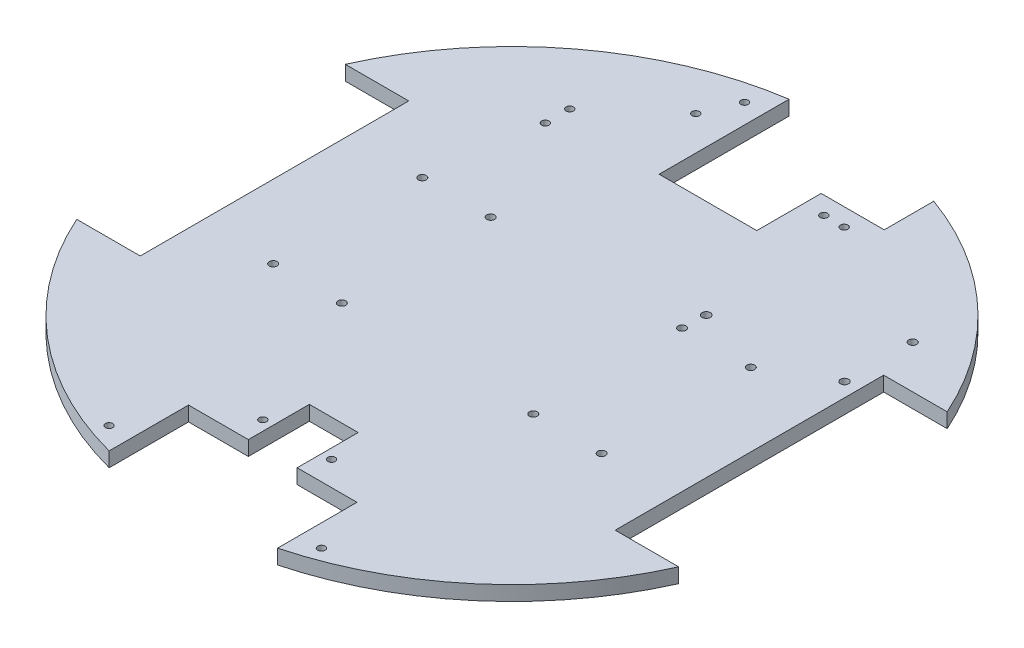
SolidWorks part; units mm, degrees
ref_plane "Plan de face" through (0, 0, 0) normal (0, 0, 1) x (1, 0, 0)
ref_plane "Plan de dessus" through (0, 0, 0) normal (0, 1, 0) x (1, 0, 0)
ref_plane "Plan de droite" through (0, 0, 0) normal (1, 0, 0) x (0, 0, -1)
sketch "Esquisse1" plane through (0, 0, 0) normal (0, 1, 0) x (1, 0, 0)
  circle A0 centre (0, 0) radius 135
  dimension "D1" = 270
extrude "Boss.-Extru.1" add sketch "Esquisse1" along normal blind 6 contours A0
sketch "Esquisse2" plane through (0, 6, 0) normal (0, 1, 0) x (1, 0, 0)
  line L0 (0, 135) -> (0, -135) construction
  line L9 (-123.2883, 55) -> (123.2883, 55) construction
  line L18 (123.2883, -55) -> (-123.2883, -55) construction
  line L20 (97.2883, 55) -> (209.472, 55)
  line L21 (97.2883, 55) -> (97.2883, -55)
  line L22 (97.2883, -55) -> (209.472, -55)
  line L23 (209.472, 55) -> (209.472, -55)
  line L24 (-97.2883, 55) -> (-208.1921, 55)
  line L25 (-97.2883, 55) -> (-97.2883, -55)
  line L26 (-97.2883, -55) -> (-208.1921, -55)
  line L27 (-208.1921, 55) -> (-208.1921, -55)
  circle A0 centre (0, 0) radius 135 construction
  dimension "D1" = 55
  dimension "D2" = 55
  dimension "D3" = 26
  dimension "D4" = 26
extrude "Enlèv. mat.-Extru.12" cut sketch "Esquisse2" against normal blind 10
sketch "Esquisse3" plane through (0, 6, 0) normal (0, 1, 0) x (1, 0, 0)
  line L0 (0, -135) -> (0, 80.2874) construction
  line L1 (10, -98) -> (34.5, -98)
  line L2 (-10, -98) -> (-10, -73)
  line L9 (-20, 80.2874) -> (-20, 135)
  line L10 (-20, 80.2874) -> (20, 80.2874)
  line L14 (-34.5, -98) -> (-34.5, -135)
  line L15 (-34.5, -98) -> (-10, -98)
  line L17 (-34.5, -135) -> (34.5, -135)
  line L18 (34.5, -98) -> (34.5, -135)
  line L19 (10, -98) -> (10, -73)
  line L20 (10, -73) -> (-10, -73)
  line L28 (20, 106.6624) -> (20, 80.2874)
  line L33 (0, 135) -> (0, 1189.7126) construction
  line L34 (-20, 135) -> (45.8353, 135)
  line L37 (45.8353, 106.6624) -> (45.8353, 135)
  line L38 (45.8353, 106.6624) -> (20, 106.6624)
  arc A1 (-123.2883, -55) -> (123.2883, -55) centre (0, 0) ccw construction
  arc A2 (123.2883, 55) -> (-123.2883, 55) centre (0, 0) ccw construction
  dimension "D1" = 25
  dimension "D2" = 54.7126
  dimension "D3" = 40
  dimension "D4" = 20
  dimension "D5" = 69
  dimension "D6" = 37
  dimension "D7" = 20
extrude "Enlèv. mat.-Extru.13" cut sketch "Esquisse3" against normal through all
sketch "Esquisse4" plane through (0, 6, 0) normal (0, 1, 0) x (1, 0, 0)
  circle A16 centre (91.5259, 44.7102) radius 1.6533
  circle A17 centre (91.5297, 72.638) radius 1.6241
  circle A18 centre (39.6069, 39.9742) radius 1.712
  circle A20 centre (67.2883, 30.5487) radius 1.6
  circle A21 centre (39.2883, 30.4123) radius 1.6
  circle A22 centre (39.2883, -30.5471) radius 1.6
  circle A23 centre (67.2883, -30.5471) radius 1.6
  circle A24 centre (-39.2883, -30.4123) radius 1.6
  circle A25 centre (-67.2883, -30.5487) radius 1.6
  circle A26 centre (-67.2883, 30.5471) radius 1.6
  circle A27 centre (-39.2883, 30.5471) radius 1.6
  circle A44 centre (-61.4629, 85.131) radius 1.5
  circle A45 centre (-61.4629, 75.131) radius 1.5
  circle A50 centre (-28, 123.2874) radius 1.5
  circle A51 centre (-34, 109.2874) radius 1.5
  circle A57 centre (28.3333, 99.4174) radius 1.5
  circle A58 centre (36.6667, 99.4174) radius 1.5
  circle A60 centre (43.5, -121.5622) radius 1.5
  circle A61 centre (-43.5, -121.5622) radius 1.5
  circle A62 centre (14.08, -88) radius 1.5
  circle A63 centre (-14.0701, -88) radius 1.5
  point P19 (-14.0632, -89)
  dimension "D8" = 3
extrude "Enlèv. mat.-Extru.14" cut sketch "Esquisse4" against normal through all both and the other way through all
